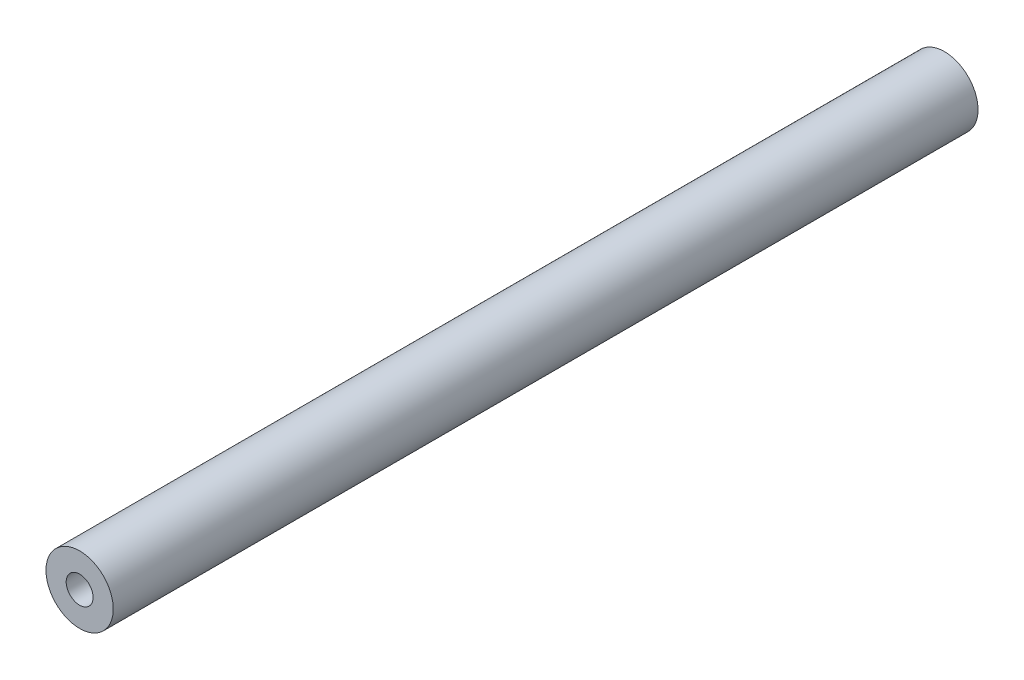
SolidWorks part; units mm, degrees
ref_plane "Ebene vorne" through (0, 0, 0) normal (0, 0, 1) x (1, 0, 0)
ref_plane "Ebene oben" through (0, 0, 0) normal (0, 1, 0) x (1, 0, 0)
ref_plane "Ebene rechts" through (0, 0, 0) normal (1, 0, 0) x (0, 0, -1)
sketch "Skizze1" plane through (0, 0, 0) normal (0, 0, 1) x (1, 0, 0)
  circle A0 centre (0, 0) radius 3.5
  dimension "D1" = 7
extrude "Aufsatz-Linear austragen1" add sketch "Skizze1" along normal blind 90
sketch "Skizze3" plane through (0, 0, 90) normal (0, 0, 1) x (1, 0, 0)
  circle A0 centre (0, 0) radius 1.4
  dimension "D1" = 2.8
extrude "Schnitt-Linear austragen1" cut sketch "Skizze3" against normal blind 10
sketch "Skizze4" plane through (0, 0, 0) normal (0, 0, -1) x (-1, 0, 0)
  circle A0 centre (0, 0) radius 1.4
  dimension "D1" = 2.8
extrude "Schnitt-Linear austragen2" cut sketch "Skizze4" against normal blind 10
